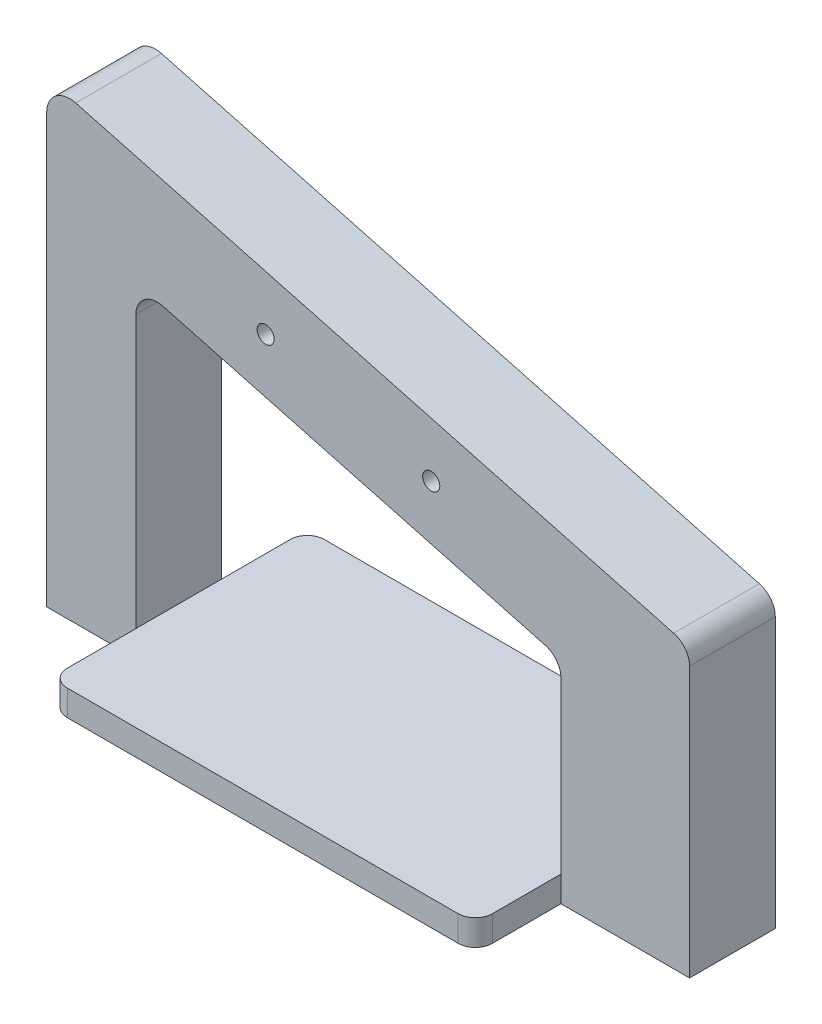
SolidWorks part; units mm, degrees
ref_plane "Front Plane" through (0, 0, 0) normal (0, 0, 1) x (1, 0, 0)
ref_plane "Top Plane" through (0, 0, 0) normal (0, 1, 0) x (1, 0, 0)
ref_plane "Right Plane" through (0, 0, 0) normal (1, 0, 0) x (0, 0, -1)
sketch "Sketch1" plane through (0, 0, 0) normal (0, 0, 1) x (1, 0, 0)
  line L5 (-101.6, -7.62) -> (-101.6, 119.38)
  line L6 (84.1935, 78.5133) -> (-92.9873, 125.9888)
  line L8 (88.9, -7.62) -> (88.9, 72.3797)
  line L9 (0, 0) -> (50.8, 0)
  line L10 (0, 0) -> (-75.1875, 0)
  line L11 (-75.1875, 0) -> (-75.1875, 80.6245)
  line L12 (-67.194, 86.7581) -> (46.0935, 56.4029)
  line L14 (0, 0) -> (0, -7.62) construction
  line L15 (0, -7.62) -> (-101.6, -7.62)
  line L16 (0, -7.62) -> (88.9, -7.62)
  line L17 (50.8, 50.2692) -> (50.8, 0)
  arc A0 (84.1935, 78.5133) -> (88.9, 72.3797) centre (82.55, 72.3797) cw
  arc A3 (-101.6, 119.38) -> (-92.9873, 125.9888) centre (-94.7581, 119.38) cw
  arc A4 (46.0935, 56.4029) -> (50.8, 50.2692) centre (44.45, 50.2692) cw
  arc A5 (-75.1875, 80.6245) -> (-67.194, 86.7581) centre (-68.8375, 80.6245) cw
  dimension "D2" = 6.35
  dimension "D1" = 6.35
extrude "Boss-Extrude1" add sketch "Sketch1" along normal blind 25.4
sketch "Sketch2" plane through (0, 0, 25.4) normal (0, 0, 1) x (1, 0, 0)
  line L0 (-75.1875, 0) -> (-75.1875, -7.62)
  line L1 (-101.6, -7.62) -> (88.9, -7.62) construction
  line L2 (50.8, 0) -> (50.8, -7.62)
  line L3 (-75.1875, 0) -> (50.8, 0)
  line L4 (-75.1875, -7.62) -> (50.8, -7.62)
extrude "Boss-Extrude2" add sketch "Sketch2" along normal blind 25.4
fillet "Fillet1" radius 5.08 2 edges at (-75.1875, -3.81, 50.8) (50.8, -3.81, 50.8)
sketch "Sketch3" plane through (0, 0, 0) normal (0, 0, -1) x (-1, 0, 0)
  line L0 (75.1875, -7.62) -> (75.1875, 0) construction
  line L1 (-50.8, 0) -> (-50.8, -7.62) construction
  line L2 (75.1875, -7.62) -> (75.1875, 0)
  line L3 (-50.8, 0) -> (-50.8, -7.62)
  line L4 (-50.8, 0) -> (75.1875, 0)
  line L5 (-50.8, -7.62) -> (75.1875, -7.62)
extrude "Boss-Extrude3" add sketch "Sketch3" along normal blind 25.4
fillet "Fillet2" radius 5.08 2 edges at (-75.1875, -3.81, -25.4) (50.8, -3.81, -25.4)
sketch "Sketch4" plane through (0, 0, 25.4) normal (0, 0, 1) x (1, 0, 0)
  line L0 (-12.1938, 0) -> (-12.1938, 72.0209) construction
  line L1 (45.72, 0) -> (-70.1075, 0) construction
  line L2 (46.0935, 56.4029) -> (-67.194, 86.7581) construction
  line L3 (-12.1938, 72.0209) -> (-12.1938, 104.3402) construction
  line L4 (84.1935, 78.5133) -> (-92.9873, 125.9888) construction
  line L5 (-12.1938, 88.1806) -> (-36.7283, 94.7546) construction
  line L6 (-12.1938, 88.1806) -> (12.3408, 81.6066) construction
  circle A0 centre (-36.7283, 94.7546) radius 2.54
  circle A1 centre (12.3408, 81.6066) radius 2.54
  dimension "D1" = 5.08
  dimension "D2" = 5.08
extrude "Cut-Extrude1" cut sketch "Sketch4" against normal through all
